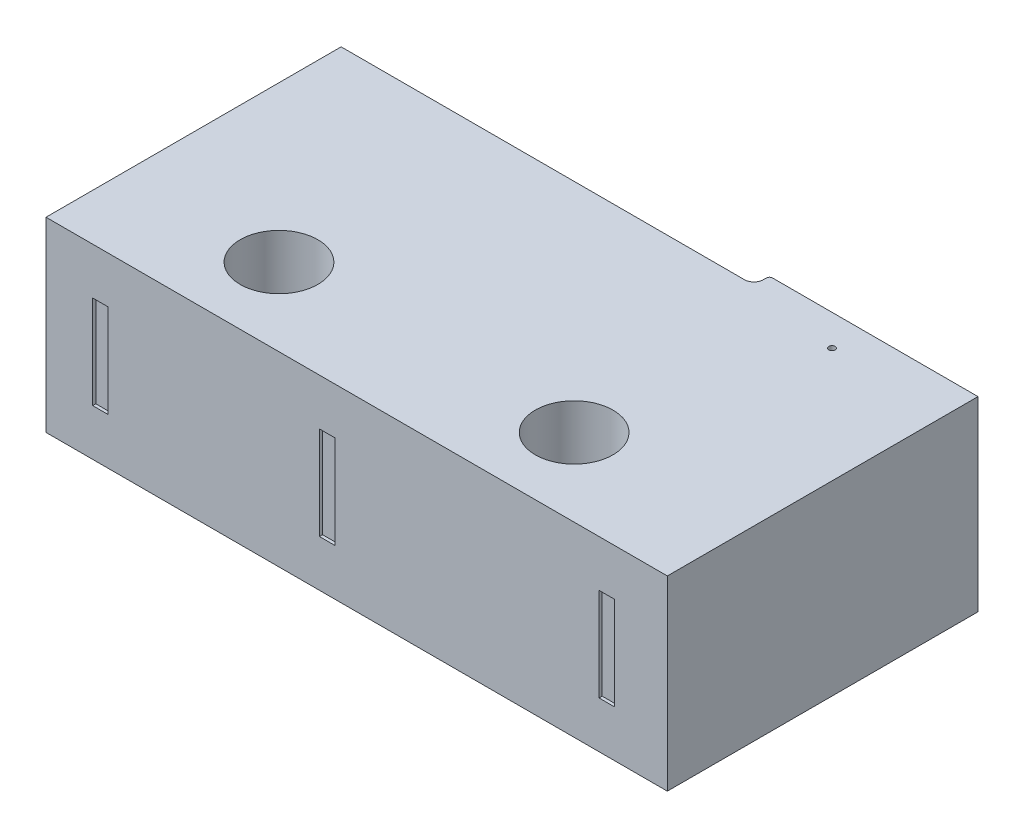
SolidWorks part; units mm, degrees
material "Plástico personalizado"
ref_plane "Alzado" through (0, 0, 0) normal (0, 0, 1) x (1, 0, 0)
ref_plane "Planta" through (0, 0, 0) normal (0, 1, 0) x (1, 0, 0)
ref_plane "Vista lateral" through (0, 0, 0) normal (1, 0, 0) x (0, 0, -1)
sketch "Croquis1" plane through (0, 0, 0) normal (0, 1, 0) x (1, 0, 0)
  line L0 (-10, 4.5) -> (-10, 5)
  line L1 (10, -5) -> (-10, -5)
  line L2 (10, -5) -> (10, 5)
  line L3 (10, 5) -> (-10, 5)
  line L4 (-10, -5) -> (-10, 5)
  line L5 (10, -5) -> (-10, 5) construction
  line L6 (10, 5) -> (-10, -5) construction
  line L7 (-10, 4.5) -> (2.9867, 4.5)
  line L8 (3.2867, 4.8) -> (3.2867, 5)
  line L9 (3.2867, 5) -> (10, 5)
  arc A0 (3.2867, 4.8) -> (2.9867, 4.5) centre (2.9867, 4.8) cw
  point P0 (0, 0)
  dimension "D4" = 0.3
  dimension "D1" = 10
  dimension "D2" = 20
  dimension "D3" = 0.5
extrude "Saliente-Extruir2" add sketch "Croquis1" along normal blind 6 contours L8 A0 L7 L4 L1 L2 L3
sketch "Croquis2" plane through (0, 6, 0) normal (0, 1, 0) x (1, 0, 0)
  line L3 (10, -5) -> (10, 5) construction
  circle A0 centre (-5, -2.5) radius 1.25
  circle A1 centre (4.5, -2.5) radius 1.25
  dimension "D1" = 2.5
  dimension "D2" = 2.5
  dimension "D3" = 9.5
  dimension "D4" = 5
  dimension "D5" = 5.5
extrude "Cortar-Extruir1" cut sketch "Croquis2" against normal blind 10
fillet "Redondeo1" radius 0.1 1 edges at (3.2867, 3, -5)
sketch "Croquis3" plane through (0, 0, -4.5) normal (0, 0, -1) x (-1, 0, 0)
  line L0 (-3.3867, 0) -> (-3.3867, 6) construction
  line L1 (0.6133, 1.35) -> (-1.3867, 1.35)
  line L2 (0.6133, 1.35) -> (0.6133, 4.65)
  line L3 (0.6133, 4.65) -> (-1.3867, 4.65)
  line L4 (-1.3867, 1.35) -> (-1.3867, 4.65)
  line L5 (0.6133, 1.35) -> (-1.3867, 4.65) construction
  line L6 (0.6133, 4.65) -> (-1.3867, 1.35) construction
  line L8 (10, 0) -> (-2.9867, 0) construction
  point P0 (-0.3867, 3)
  dimension "D1" = 2
  dimension "D2" = 2
  dimension "D3" = 3.3
  dimension "D4" = 3
extrude "Cortar-Extruir2" cut sketch "Croquis3" against normal blind 5
sketch "Croquis4" plane through (0, 6, 0) normal (0, 1, 0) x (1, 0, 0)
  line L0 (10, 4) -> (6.3, 4)
  line L1 (10, -5) -> (10, 5) construction
  line L2 (10, 5) -> (10, 4)
  circle A0 centre (6.3, 4) radius 0.1
  dimension "D3" = 0.2
  dimension "D1" = 3.7
  dimension "D2" = 1
extrude "Cortar-Extruir3" cut sketch "Croquis4" against normal up to surface (6 mm away) up to face at (-5, 0, 3.75)
sketch "Croquis5" plane through (0, 0, 5) normal (0, 0, 1) x (1, 0, 0)
  line L0 (-10, 3) -> (10, 3) construction
  line L1 (-10, 6) -> (-10, 0) construction
  line L2 (10, 6) -> (10, 0) construction
  line L4 (-7.9972, 1.5) -> (-8.4972, 1.5)
  line L5 (-7.9972, 1.5) -> (-7.9972, 4.5)
  line L6 (-7.9972, 4.5) -> (-8.4972, 4.5)
  line L7 (-8.4972, 1.5) -> (-8.4972, 4.5)
  line L8 (-7.9972, 1.5) -> (-8.4972, 4.5) construction
  line L9 (-7.9972, 4.5) -> (-8.4972, 1.5) construction
  line L10 (-0.6972, 1.5) -> (-1.1972, 1.5)
  line L11 (-0.6972, 1.5) -> (-0.6972, 4.5)
  line L12 (-0.6972, 4.5) -> (-1.1972, 4.5)
  line L13 (-1.1972, 1.5) -> (-1.1972, 4.5)
  line L14 (-0.6972, 1.5) -> (-1.1972, 4.5) construction
  line L15 (-0.6972, 4.5) -> (-1.1972, 1.5) construction
  line L16 (8.3028, 1.5) -> (7.8028, 1.5)
  line L17 (8.3028, 1.5) -> (8.3028, 4.5)
  line L18 (8.3028, 4.5) -> (7.8028, 4.5)
  line L19 (7.8028, 1.5) -> (7.8028, 4.5)
  line L20 (8.3028, 1.5) -> (7.8028, 4.5) construction
  line L21 (8.3028, 4.5) -> (7.8028, 1.5) construction
  point P6 (-8.2472, 3)
  point P11 (-0.9472, 3)
  point P16 (8.0528, 3)
  dimension "D1" = 0.5
  dimension "D2" = 0.5
  dimension "D3" = 0.5
  dimension "D4" = 3
  dimension "D5" = 3
  dimension "D6" = 3
  dimension "D7" = 7.8
  dimension "D8" = 9.5
extrude "Cortar-Extruir4" cut sketch "Croquis5" against normal blind 0.1
